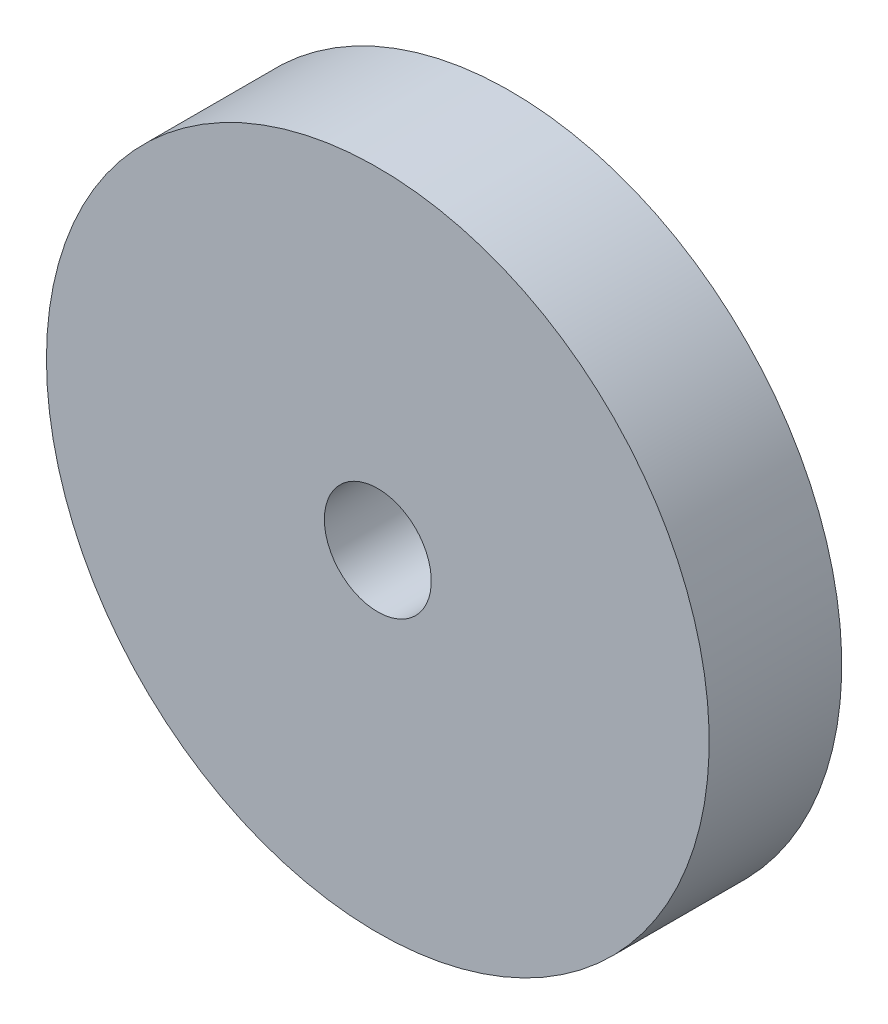
SolidWorks part; units mm, degrees
ref_plane "Front Plane" through (0, 0, 0) normal (0, 0, 1) x (1, 0, 0)
ref_plane "Top Plane" through (0, 0, 0) normal (0, 1, 0) x (1, 0, 0)
ref_plane "Right Plane" through (0, 0, 0) normal (1, 0, 0) x (0, 0, -1)
sketch "Sketch1" plane through (0, 0, 0) normal (0, 0, 1) x (1, 0, 0)
  circle A0 centre (0, 0) radius 15.5
  circle A1 centre (0, 0) radius 2.5
  dimension "D1" = 5
  dimension "D2" = 31
extrude "Boss-Extrude1" add sketch "Sketch1" along normal blind 6.2
